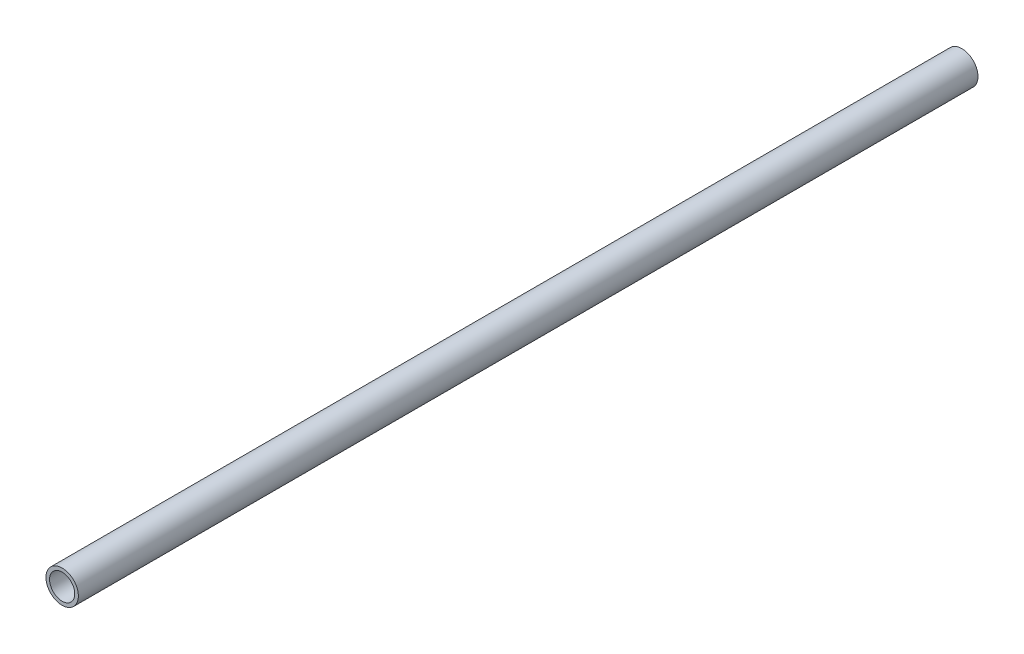
SolidWorks part; units mm, degrees
ref_plane "Front Plane" through (0, 0, 0) normal (0, 0, 1) x (1, 0, 0)
ref_plane "Top Plane" through (0, 0, 0) normal (0, 1, 0) x (1, 0, 0)
ref_plane "Right Plane" through (0, 0, 0) normal (1, 0, 0) x (0, 0, -1)
sketch "Sketch1" plane through (0, 0, 0) normal (0, 0, 1) x (1, 0, 0)
  line L0 (-4.5, 0) -> (4.5, 0) construction
  line L1 (-3.5, 0) -> (3.5, 0) construction
  circle A0 centre (0, 0) radius 4.5 construction
  circle A1 centre (0, 0) radius 3.5 construction
  point P4 (0, 0)
  point P10 (0, 0)
  dimension "ID" = 7
  dimension "OD" = 9
  dimension "Wall Thickness" = 1
sketch "Sketch2" plane through (0, 0, 0) normal (1, 0, 0) x (0, 0, -1)
  line L0 (150, 0) -> (-150, 0) construction
  line L2 (-150, -4.5) -> (150, -4.5) construction
  line L3 (-150, -4.5) -> (-150, 4.5) construction
  line L4 (-150, 4.5) -> (150, 4.5) construction
  line L5 (150, -4.5) -> (150, 4.5) construction
  line L6 (0, 4.5) -> (0, -4.5) construction
  line L7 (-150, 0) -> (150, 0) construction
  point P0 (-134.25, 0)
  point P3 (0, 0)
  point P4 (0, 0)
  point P6 (134.25, 0)
  dimension "D2" = 15.75
  dimension "D3" = 15.75
  dimension "Length" = 300
sketch "Sketch3" plane through (0, 0, 0) normal (0, 0, 1) x (1, 0, 0)
  circle A0 centre (0, 0) radius 4.5
  circle A1 centre (0, 0) radius 3.5 construction
  circle A2 centre (0, 0) radius 3.5
  dimension "D1" = 9
extrude "Boss-Extrude1" add sketch "Sketch3" along normal mid plane 300
sketch "Sketch4" plane through (0, 0, 150) normal (0, 0, 1) x (1, 0, 0)
  circle A0 centre (0, 0) radius 4.5
  circle A1 centre (0, 0) radius 4.5 construction
extrude "Cut-Extrude1" cut sketch "Sketch4" against normal blind 50
equation "\"D2@Sketch2\" = \"OD@Sketch1\" * 1.75"
equation "\"D3@Sketch2\"=\"D2@Sketch2\""
equation "\"D1@Sketch3\" = \"OD@Sketch1\""
equation "\"D1@Boss-Extrude1\"=\"Length@Sketch2\""
